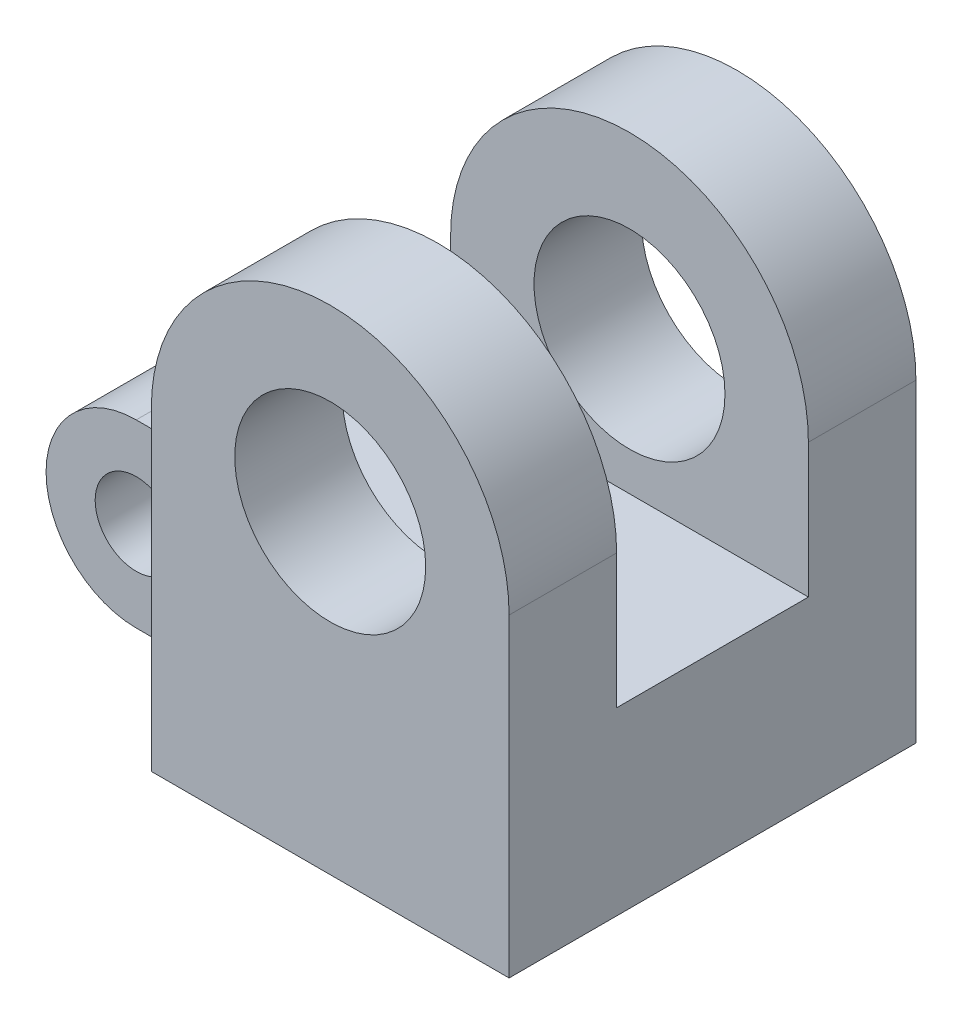
SolidWorks part; units mm, degrees
ref_plane "Front Plane" through (0, 0, 0) normal (0, 0, 1) x (1, 0, 0)
ref_plane "Top Plane" through (0, 0, 0) normal (0, 1, 0) x (1, 0, 0)
ref_plane "Right Plane" through (0, 0, 0) normal (1, 0, 0) x (0, 0, -1)
sketch "Sketch1" plane through (0, 0, 0) normal (0, 0, 1) x (1, 0, 0)
  line L0 (-7.1385, -12.5438) -> (-7.1385, 0)
  line L1 (7.1385, 0) -> (7.1385, -12.5438)
  line L2 (7.1385, -12.5438) -> (-7.1385, -12.5438)
  arc A0 (-7.1385, 0) -> (7.1385, 0) centre (0, 0) cw
extrude "Extrude1" add sketch "Sketch1" along normal mid plane 16.2338
sketch "Sketch2" plane through (0, 0, 0) normal (0, 0, 1) x (1, 0, 0)
  line L1 (-29.3672, 24.4058) -> (26.7947, 24.4058)
  line L2 (-29.3672, 24.4058) -> (-29.3672, -5.3505)
  line L3 (-29.3672, -5.3505) -> (26.7947, -5.3505)
  line L4 (26.7947, 24.4058) -> (26.7947, -5.3505)
extrude "Extrude2" cut sketch "Sketch2" against normal mid plane 7.6513
sketch "Sketch3" plane through (0, 0, 8.1169) normal (0, 0, 1) x (1, 0, 0)
  circle A0 centre (0, 0) radius 3.81
  dimension "D1" = 7.62
extrude "Extrude3" cut sketch "Sketch3" against normal through all
sketch "Sketch4" plane through (0, -12.5438, 0) normal (0, -1, 0) x (1, 0, 0)
  circle A0 centre (0, 0) radius 6.425
  dimension "D1" = 12.85
extrude "Cut-Extrude1" cut sketch "Sketch4" against normal blind 1.27
sketch "Sketch6" plane through (0, 0, 0) normal (0, 0, 1) x (1, 0, 0)
  line L0 (7.1385, -12.5438) -> (7.1385, -5.3505)
  line L2 (12.396, -12.5438) -> (7.1385, -12.5438)
  line L4 (7.1385, -5.3505) -> (12.396, -5.3505)
  arc A0 (12.396, -5.3505) -> (12.396, -12.5438) centre (12.396, -8.9471) cw
  circle A1 centre (12.396, -8.9471) radius 1.6384
extrude "Extrude4" add sketch "Sketch6" along normal mid plane 6.925
mirror "Mirror1" about plane through (0, 0, 0) normal (1, 0, 0) of "Extrude4"
sketch "Sketch7" plane through (0, 0, 3.4625) normal (0, 0, 1) x (1, 0, 0)
  line L2 (7.1385, -12.5438) -> (12.396, -12.5438)
  line L3 (7.1385, -5.3505) -> (7.1385, -12.5438)
  line L4 (7.1385, -12.5438) -> (12.396, -12.5438)
  line L5 (7.1385, -5.3505) -> (7.1385, -12.5438)
  line L7 (12.396, -5.3505) -> (7.1385, -5.3505)
  line L8 (12.396, -5.3505) -> (7.1385, -5.3505)
  arc A1 (12.396, -12.5438) -> (12.396, -5.3505) centre (12.396, -8.9471) ccw
  arc A2 (12.396, -12.5438) -> (12.396, -5.3505) centre (12.396, -8.9471) ccw
  dimension "D1" = 0
extrude "Extrude5" cut sketch "Sketch7" against normal through all
